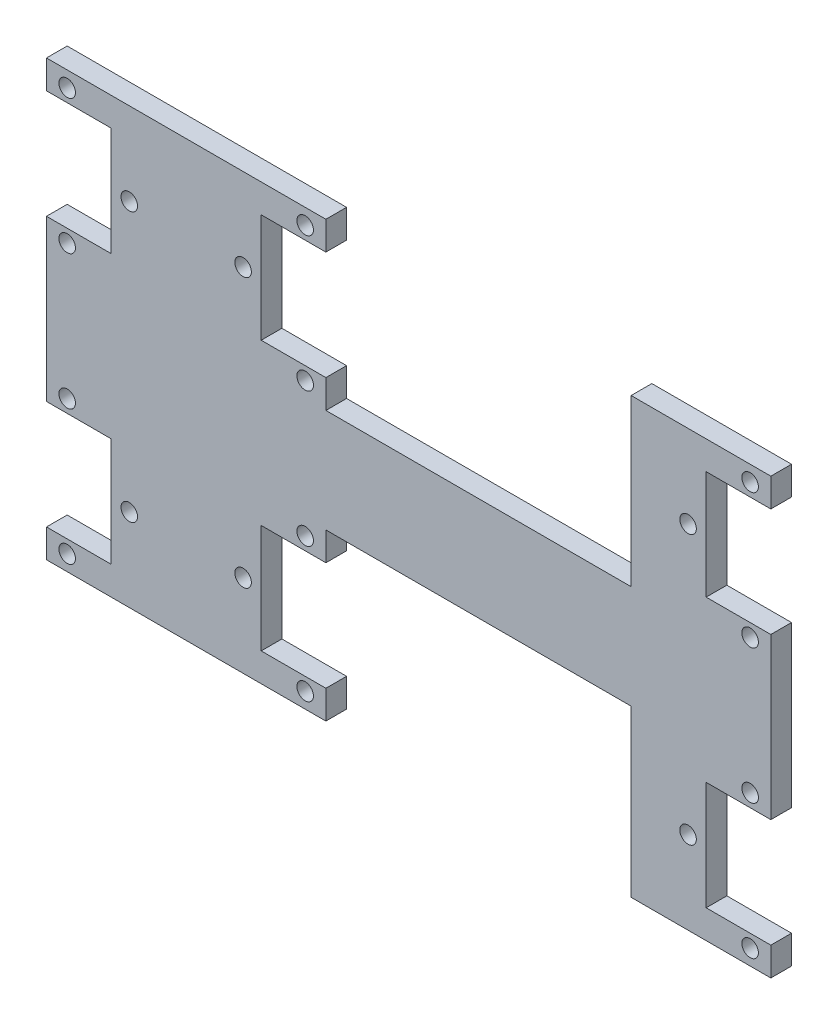
SolidWorks part; units mm, degrees
ref_plane "Front" through (0, 0, 0) normal (0, 0, 1) x (1, 0, 0)
ref_plane "Top" through (0, 0, 0) normal (0, 1, 0) x (1, 0, 0)
ref_plane "Right" through (0, 0, 0) normal (1, 0, 0) x (0, 0, -1)
sketch "Эскиз3" plane through (0, 0, 0) normal (0, 0, 1) x (1, 0, 0)
  line L0 (0, 10) -> (-16, 10) construction
  line L1 (-70, -10) -> (70, -10)
  line L2 (-70, -10) -> (-70, 10)
  line L3 (-70, 10) -> (70, 10)
  line L4 (70, -10) -> (70, 10)
  line L5 (-70, -10) -> (70, 10) construction
  line L6 (-70, 10) -> (70, -10) construction
  line L7 (-16, 15.5) -> (-16, 36.5) construction
  line L8 (-16, 10) -> (-70, 10)
  line L9 (-16, 10) -> (-16, 42)
  line L10 (-16, 42) -> (-70, 42)
  line L11 (-43, 10) -> (-43, 42)
  line L12 (-28.5, 26) -> (-32, 26) construction
  line L13 (-16, 15.5) -> (-28.5, 15.5)
  line L14 (-16, 15.5) -> (-16, 36.5)
  line L15 (-16, 36.5) -> (-28.5, 36.5)
  line L16 (-28.5, 15.5) -> (-28.5, 36.5)
  line L17 (-16, 42) -> (-16, 39) construction
  line L18 (-16, 39) -> (-20, 39) construction
  line L19 (-43, 10) -> (-43, 61.6678) construction
  line L20 (-70, 36.5) -> (-57.5, 36.5)
  line L21 (-57.5, 15.5) -> (-57.5, 36.5)
  line L22 (-70, 15.5) -> (-57.5, 15.5)
  line L23 (-70, 15.5) -> (-70, 36.5)
  line L24 (-70, 10) -> (-70, 42)
  line L25 (70, 15.5) -> (70, 36.5)
  line L26 (70, 15.5) -> (57.5, 15.5)
  line L27 (57.5, 15.5) -> (57.5, 36.5)
  line L28 (70, 36.5) -> (57.5, 36.5)
  line L29 (-70, 0) -> (0, 0) construction
  line L30 (70, 10) -> (43, 10)
  line L31 (70, 10) -> (70, 42)
  line L32 (70, 42) -> (43, 42)
  line L33 (43, 10) -> (43, 42)
  line L34 (70, -15.5) -> (57.5, -15.5)
  line L35 (57.5, -15.5) -> (57.5, -36.5)
  line L36 (70, -36.5) -> (57.5, -36.5)
  line L37 (70, -15.5) -> (70, -36.5)
  line L38 (70, -42) -> (43, -42)
  line L39 (43, -10) -> (43, -42)
  line L40 (70, -10) -> (43, -10)
  line L41 (70, -10) -> (70, -42)
  line L42 (-16, -36.5) -> (-28.5, -36.5)
  line L43 (-28.5, -15.5) -> (-28.5, -36.5)
  line L44 (-16, -15.5) -> (-28.5, -15.5)
  line L45 (-16, -15.5) -> (-16, -36.5)
  line L46 (-70, -10) -> (-70, -42)
  line L47 (-16, -42) -> (-70, -42)
  line L48 (-16, -10) -> (-16, -42)
  line L49 (-16, -10) -> (-70, -10)
  line L50 (-70, -15.5) -> (-70, -36.5)
  line L51 (-70, -15.5) -> (-57.5, -15.5)
  line L52 (-57.5, -15.5) -> (-57.5, -36.5)
  line L53 (-70, -36.5) -> (-57.5, -36.5)
  circle A0 centre (-32, 26) radius 1.6
  circle A1 centre (-20, 39) radius 1.6
  circle A2 centre (-20, 13) radius 1.6
  circle A3 centre (-66, 39) radius 1.6
  circle A4 centre (-66, 13) radius 1.6
  circle A5 centre (-54, 26) radius 1.6
  circle A6 centre (54, 26) radius 1.6
  circle A7 centre (66, 13) radius 1.6
  circle A8 centre (66, 39) radius 1.6
  circle A9 centre (66, -39) radius 1.6
  circle A10 centre (66, -13) radius 1.6
  circle A11 centre (54, -26) radius 1.6
  circle A12 centre (-20, -39) radius 1.6
  circle A13 centre (-20, -13) radius 1.6
  circle A14 centre (-32, -26) radius 1.6
  circle A15 centre (-54, -26) radius 1.6
  circle A16 centre (-66, -13) radius 1.6
  circle A17 centre (-66, -39) radius 1.6
  point P0 (0, 0)
  point P14 (-16, 26)
  dimension "D9" = 3
  dimension "D10" = 4
  dimension "D11" = 51.6678
  dimension "D1" = 20
  dimension "D2" = 140
  dimension "D3" = 2
  dimension "D4" = 27
  dimension "D5" = 32
  dimension "D6" = 12.5
  dimension "D7" = 21
  dimension "D8" = 3.5
  dimension "D12" = 27
  dimension "D13" = 70
extrude "Бобышка-Вытянуть2" add sketch "Эскиз3" along normal blind 4 contours L53 L46 L47 L48 L42 L43 L44 L1 L51 L52 A17 A14 A13 A12 A15 A16 | L41 L1 L39 L38 L36 L35 L34 A9 A10 A11 | L1 L4 L3 L8 L2 | L13 L16 L15 L9 L10 L11 L8 A0 A1 A2 | L24 L3 L11 L10 L20 L21 L22 A3 A4 A5 | L33 L3 L31 L26 L27 L28 L32 A8 A6 A7
